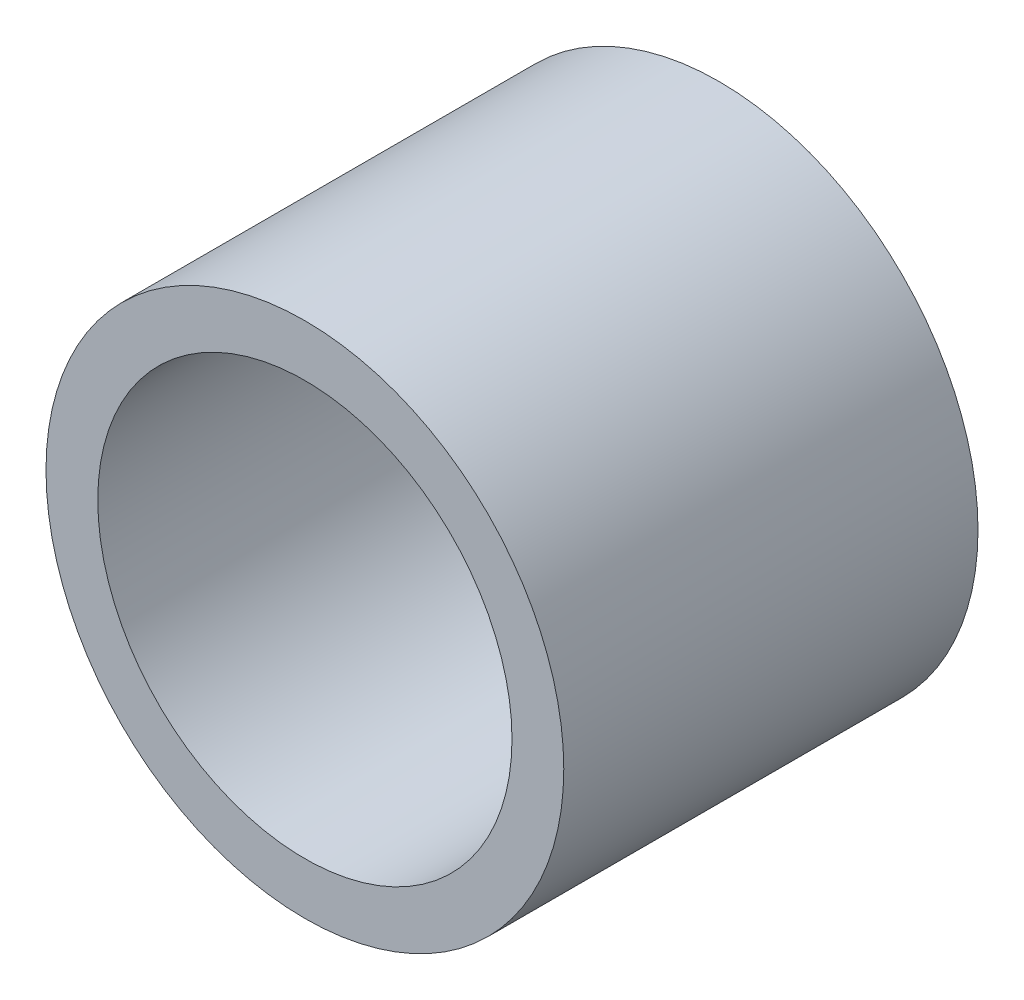
SolidWorks part; units mm, degrees
ref_plane "Front Plane" through (0, 0, 0) normal (0, 0, 1) x (1, 0, 0)
ref_plane "Top Plane" through (0, 0, 0) normal (0, 1, 0) x (1, 0, 0)
ref_plane "Right Plane" through (0, 0, 0) normal (1, 0, 0) x (0, 0, -1)
sketch "Sketch1" plane through (0, 0, 0) normal (0, 0, 1) x (1, 0, 0)
  circle A0 centre (0, 0) radius 1.25
  circle A1 centre (0, 0) radius 1
extrude "Boss-Extrude1" add sketch "Sketch1" along normal blind 2
